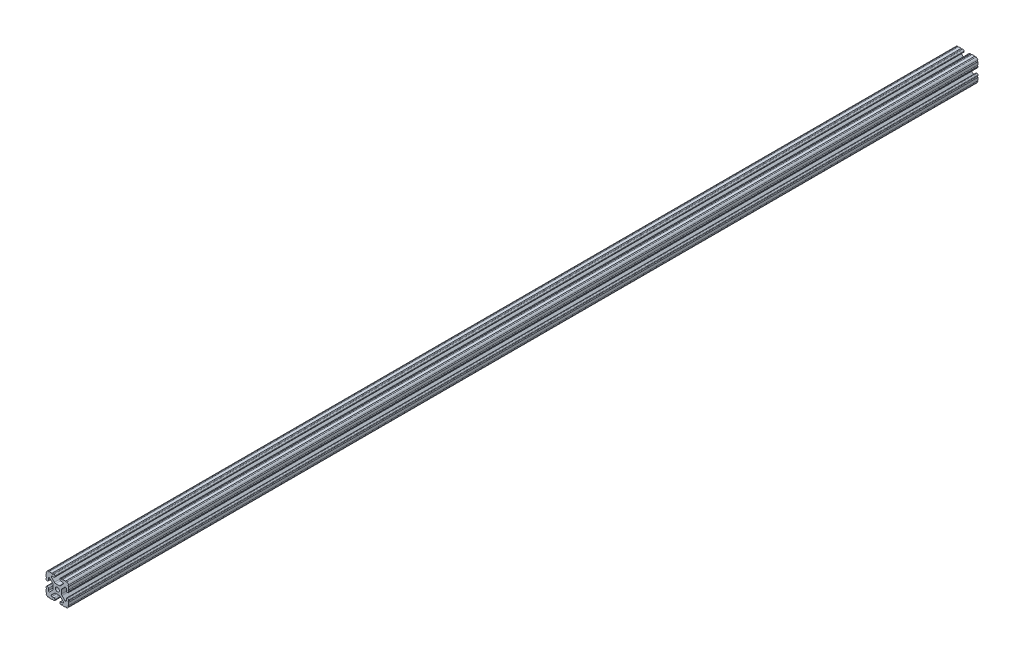
SolidWorks part; units mm, degrees
ref_plane "Front Plane" through (0, 0, 0) normal (0, 0, 1) x (1, 0, 0)
ref_plane "Top Plane" through (0, 0, 0) normal (0, 1, 0) x (1, 0, 0)
ref_plane "Right Plane" through (0, 0, 0) normal (1, 0, 0) x (0, 0, -1)
sketch "Sketch2" plane through (0, 0, 0) normal (0, 0, 1) x (1, 0, 0)
  line L0 (0, 19.05) -> (0, -19.05) construction
  line L1 (-19.05, 0) -> (19.05, 0) construction
  line L2 (4.064, -19.05) -> (19.05, -19.05)
  line L3 (19.05, -19.05) -> (19.05, -4.064)
  line L4 (4.064, -19.05) -> (4.064, -14.986)
  line L5 (4.064, -14.986) -> (12.1123, -14.986)
  line L6 (12.1123, -14.986) -> (4.1113, -6.985)
  line L7 (0, 0) -> (19.05, -19.05) construction
  line L8 (19.05, -4.064) -> (14.986, -4.064)
  line L9 (14.986, -4.064) -> (14.986, -12.1123)
  line L10 (14.986, -12.1123) -> (6.985, -4.1113)
  circle A0 centre (0, 0) radius 3.3274
  arc A1 (8.9963, -14.986) -> (9.909, -12.7826) centre (8.9963, -13.6953) ccw construction
  point P8 (0, -6.985)
  dimension "Center Hole Diameter" = 6.6548
  dimension "Rail Height" = 38.1
  dimension "Rail Width" = 38.1
  dimension "T-Slot Width" = 8.128
  dimension "Slot Inner Width" = 20.574
  dimension "Thickness" = 4.064
  dimension "Slot Depth" = 8.001
  dimension "D1" = 4.064
sketch "Sketch3" plane through (0, 0, 0) normal (1, 0, 0) x (0, 0, -1)
  line L0 (-152.4, -19.05) -> (152.4, -19.05) construction
  line L1 (-127, 0) -> (127, 0) construction
  dimension "Length" = 304.8
  dimension "D1" = 25.4
sketch "Sketch4" plane through (0, 0, 0) normal (0, 0, 1) x (1, 0, 0)
  line L0 (5.7912, -19.05) -> (14.3002, -19.05)
  line L1 (4.064, -19.05) -> (19.05, -19.05) construction
  line L2 (4.064, -19.05) -> (4.064, -14.986) construction
  line L3 (4.064, -14.986) -> (12.1123, -14.986) construction
  line L4 (4.064, -16.7132) -> (4.064, -17.3228)
  line L5 (5.7912, -14.986) -> (8.9963, -14.986)
  line L6 (0, -6.985) -> (2.833, -6.985)
  line L7 (12.1123, -14.986) -> (4.1113, -6.985) construction
  line L8 (5.0152, -7.8889) -> (9.909, -12.7826)
  line L9 (19.05, -19.05) -> (19.05, -4.064) construction
  line L10 (14.986, -12.1123) -> (6.985, -4.1113) construction
  line L11 (14.986, -4.064) -> (14.986, -12.1123) construction
  line L12 (14.986, -8.9963) -> (14.986, -5.7912)
  line L13 (19.05, -4.064) -> (14.986, -4.064) construction
  line L14 (16.7132, -4.064) -> (17.3228, -4.064)
  line L15 (19.05, -5.7912) -> (19.05, -14.3002)
  line L16 (12.7826, -9.909) -> (7.8889, -5.0152)
  line L17 (6.985, 0) -> (6.985, -2.833)
  line L18 (-19.05, 0) -> (19.05, 0) construction
  line L19 (0, -6.985) -> (0, -3.3274)
  line L20 (0, 19.05) -> (0, -19.05) construction
  line L21 (6.985, 0) -> (3.3274, 0)
  arc A0 (4.064, -17.3228) -> (5.7912, -19.05) centre (5.7912, -17.3228) ccw
  arc A2 (4.064, -16.7132) -> (5.7912, -14.986) centre (5.7912, -16.7132) cw
  arc A3 (8.9963, -14.986) -> (9.909, -12.7826) centre (8.9963, -13.6953) ccw
  arc A4 (2.833, -6.985) -> (5.0152, -7.8889) centre (2.833, -10.0711) cw
  arc A5 (14.3002, -19.05) -> (19.05, -14.3002) centre (14.3002, -14.3002) ccw
  arc A6 (12.7826, -9.909) -> (14.986, -8.9963) centre (13.6953, -8.9963) ccw
  arc A7 (14.986, -5.7912) -> (16.7132, -4.064) centre (16.7132, -5.7912) cw
  arc A8 (17.3228, -4.064) -> (19.05, -5.7912) centre (17.3228, -5.7912) cw
  arc A9 (7.8889, -5.0152) -> (6.985, -2.833) centre (10.0711, -2.833) cw
  circle A10 centre (0, 0) radius 3.3274 construction
  arc A11 (0, -3.3274) -> (3.3274, 0) centre (0, 0) ccw
  dimension "D1" = 4.7498
  dimension "D2" = 3.0861
  dimension "D3" = 1.7272
extrude "Boss-Extrude1" add sketch "Sketch4" along normal mid plane 1524
sketch "Sketch5" plane through (0, 0, 0) normal (0, 0, 1) x (1, 0, 0)
  line L0 (4.064, -19.05) -> (19.05, -19.05) construction
  line L1 (5.7912, -14.986) -> (8.9963, -14.986) construction
  line L3 (0, 0) -> (19.05, -19.05) construction
  line L4 (8.9963, -14.986) -> (8.9963, -19.05) construction
  line L5 (12.1123, -14.986) -> (4.1113, -6.985) construction
  circle A0 centre (14.7395, -19.05) radius 1.016
  circle A1 centre (7.9803, -19.05) radius 1.016
  circle A2 centre (19.05, -14.7395) radius 1.016
  circle A3 centre (19.05, -7.9803) radius 1.016
  point P10 (7.3938, -14.986)
  point P12 (13.6953, -8.9963)
extrude "Cut-Extrude1" cut sketch "Sketch5" against normal through all both and the other way through all
mirror "Mirror1" about plane through (0, 0, 0) normal (1, 0, 0) of bodies 137 134
mirror "Mirror2" about plane through (0, 0, 0) normal (0, 1, 0) of bodies 135
equation "\"D1@Boss-Extrude1\"=\"Length@Sketch3\""
equation "\"D1@Sketch2\"=\"Thickness@Sketch2\""
equation "\"D2@Sketch4\"=\"Slot Inner Width@Sketch2\"*0.15"
equation "\"D1@Sketch4\"=\"D3@Sketch4\"*2.75"
equation "\"D3@Sketch4\"=\"Thickness@Sketch2\"*0.425"
equation "\"D1@Sketch5\"=\"Thickness@Sketch2\"*0.5"
